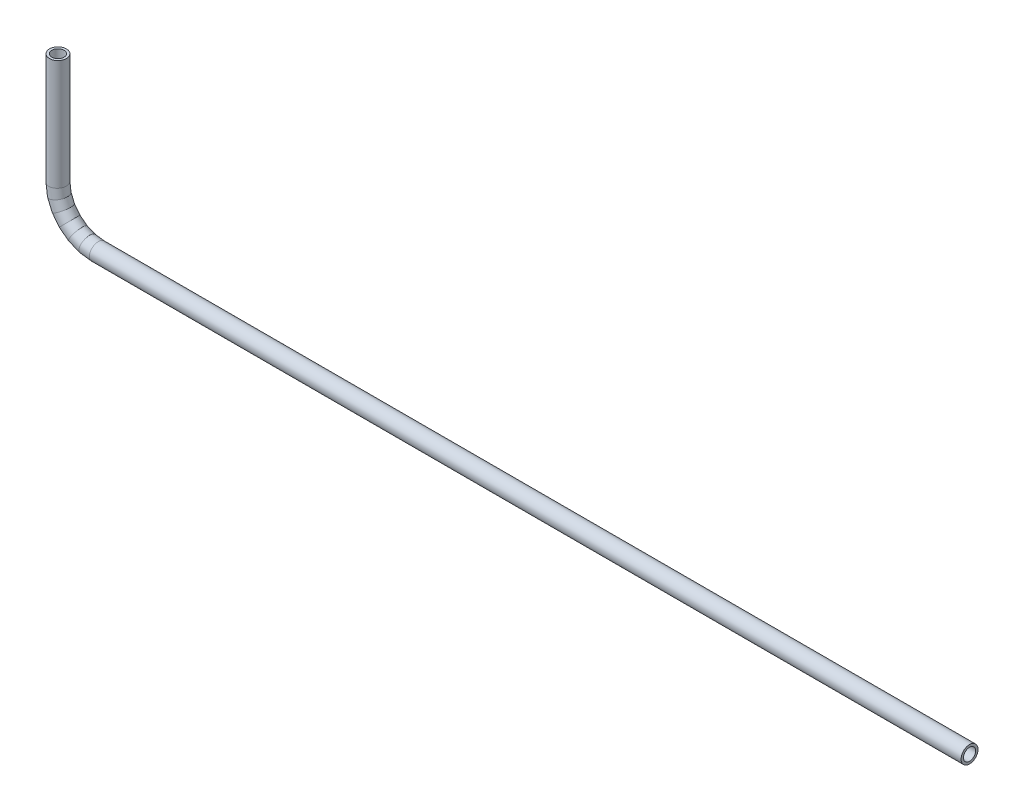
SolidWorks part; units mm, degrees
ref_plane "Front Plane" through (0, 0, 0) normal (0, 0, 1) x (1, 0, 0)
ref_plane "Top Plane" through (0, 0, 0) normal (0, 1, 0) x (1, 0, 0)
ref_plane "Right Plane" through (0, 0, 0) normal (1, 0, 0) x (0, 0, -1)
sketch3d "Path"
  line L0 (-3361.6428, -88, 0) -> (-3689.1928, -88, 0)
  line L1 (-3689.1928, -88, 0) -> (-3693.0751, -87.4889, 0)
  line L2 (-3693.0751, -87.4889, 0) -> (-3696.6928, -85.9904, 0)
  line L3 (-3696.6928, -85.9904, 0) -> (-3699.7994, -83.6066, 0)
  line L4 (-3699.7994, -83.6066, 0) -> (-3702.1832, -80.5, 0)
  line L5 (-3702.1832, -80.5, 0) -> (-3703.6817, -76.8823, 0)
  line L6 (-3703.6817, -76.8823, 0) -> (-3704.1928, -73, 0)
  line L7 (-3704.1928, -73, 0) -> (-3704.1928, -31.3, 0)
ref_plane "Start Plane" through (-3361.6428, 0, 0) normal (1, 0, 0) x (0, 0, -1)
sketch "Profile" plane through (-3361.6428, 0, 0) normal (1, 0, 0) x (0, 0, -1)
  circle A0 centre (0, -88) radius 3.175
  circle A1 centre (0, -88) radius 2.286
sweep "Tube" add profiles "Profile" path "Path"
